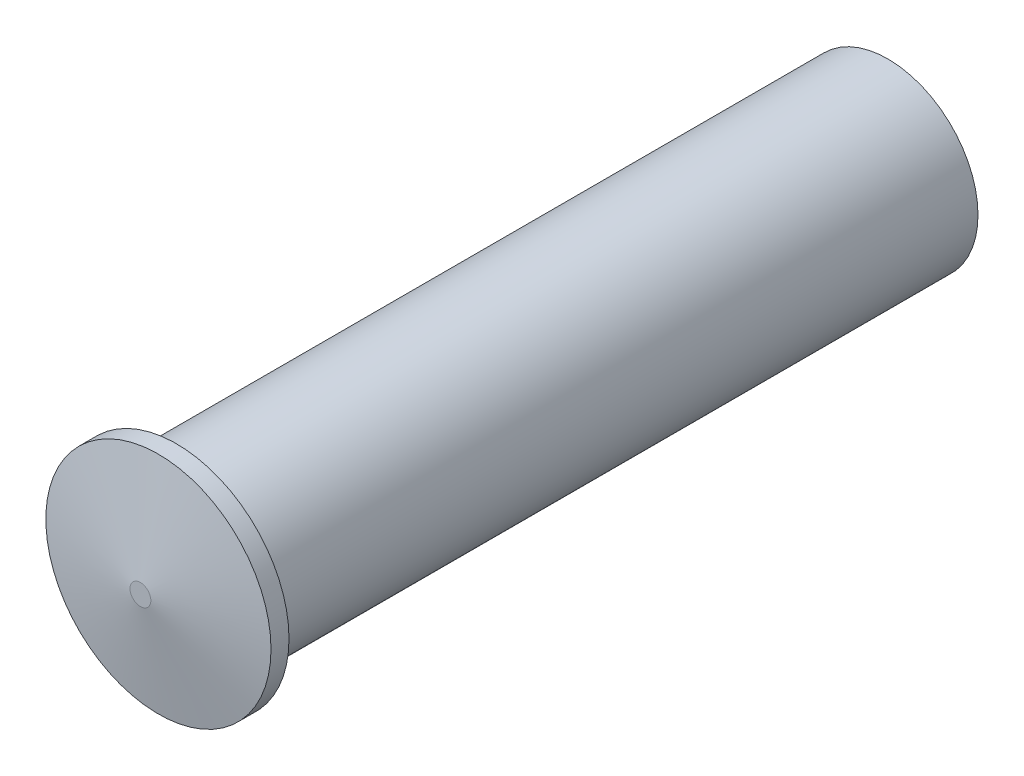
SolidWorks part; units mm, degrees
ref_plane "Front Plane" through (0, 0, 0) normal (0, 0, 1) x (1, 0, 0)
ref_plane "Top Plane" through (0, 0, 0) normal (0, 1, 0) x (1, 0, 0)
ref_plane "Right Plane" through (0, 0, 0) normal (1, 0, 0) x (0, 0, -1)
sketch "Sketch1" plane through (0, 0, 0) normal (0, 0, 1) x (1, 0, 0)
  line L0 (0, -44.5788) -> (0, 47.9169) construction
  line L1 (53.8578, 0) -> (-57.3712, 0) construction
  circle A0 centre (0, 0) radius 10
sketch "Sketch2" plane through (0, 0, 0) normal (0, 1, 0) x (1, 0, 0)
  line L0 (0, 172.8456) -> (0, -46.9914) construction
extrude "Boss-Extrude2" add sketch "Sketch1" against normal blind 79
sketch "Sketch5" plane through (0, 0, 0) normal (0, 0, 1) x (1, 0, 0)
  circle A0 centre (0, 0) radius 12.5
extrude "Boss-Extrude3" add sketch "Sketch5" along normal blind 2
sketch "Sketch6" plane through (0, 0, 2) normal (0, 0, 1) x (1, 0, 0)
  circle A1 centre (0, 0) radius 12.5
extrude "Boss-Extrude4" add sketch "Sketch6" along normal blind 2 draft 80
sketch "Sketch7" plane through (0, 0, -79) normal (0, 0, -1) x (-1, 0, 0)
  circle A0 centre (0, 0) radius 8
extrude "Cut-Extrude1" cut sketch "Sketch7" against normal blind 79
